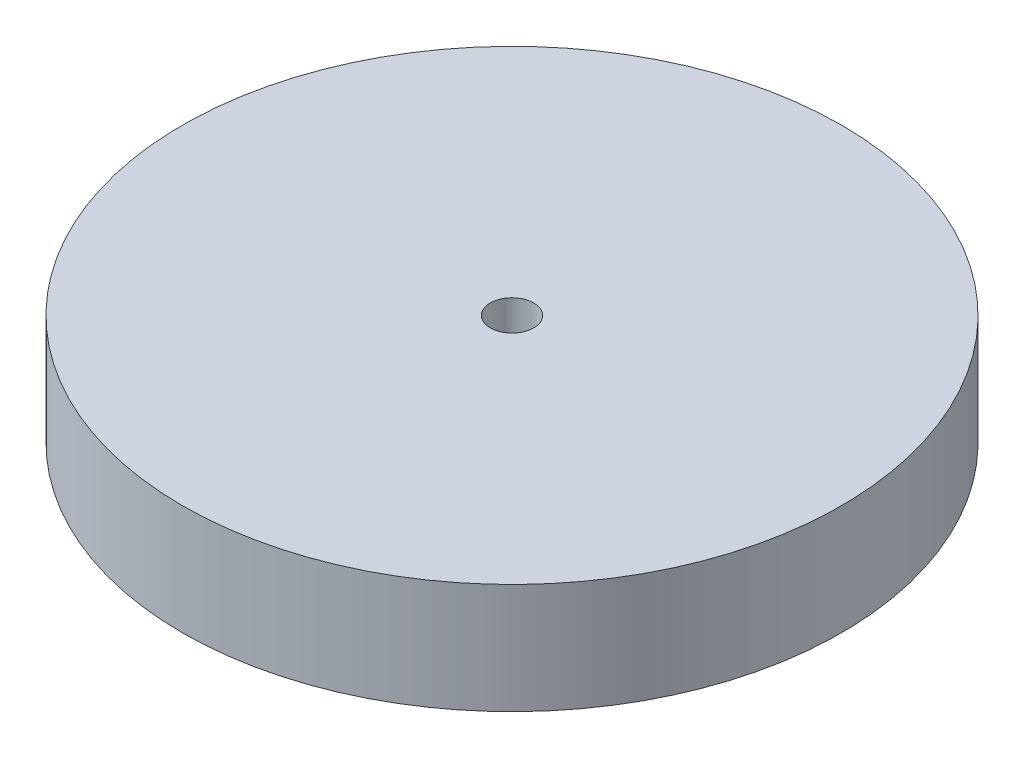
SolidWorks part; units mm, degrees
ref_plane "Front Plane" through (0, 0, 0) normal (0, 0, 1) x (1, 0, 0)
ref_plane "Top Plane" through (0, 0, 0) normal (0, 1, 0) x (1, 0, 0)
ref_plane "Right Plane" through (0, 0, 0) normal (1, 0, 0) x (0, 0, -1)
other "Default"
sketch "Sketch1" plane through (0, 0, 0) normal (0, 1, 0) x (1, 0, 0)
  circle A0 centre (0, 0) radius 2.5
  circle A1 centre (0, 0) radius 38
  dimension "ID" = 5
  dimension "OD" = 76
extrude "Boss-Extrude1" add sketch "Sketch1" along normal mid plane 12.7
